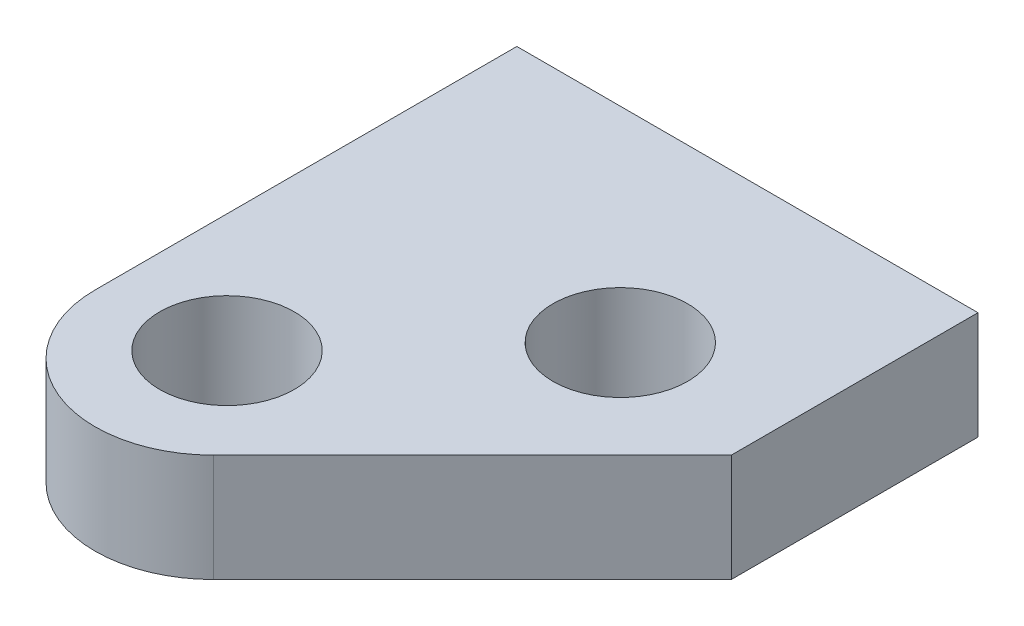
SolidWorks part; units mm, degrees
ref_plane "Piano frontale" through (0, 0, 0) normal (0, 0, 1) x (1, 0, 0)
ref_plane "Piano superiore" through (0, 0, 0) normal (0, 1, 0) x (1, 0, 0)
ref_plane "Piano destro" through (0, 0, 0) normal (1, 0, 0) x (0, 0, -1)
sketch "Schizzo1" plane through (0, 0, 0) normal (0, 1, 0) x (1, 0, 0)
  line L0 (0, 0) -> (0, -37.9)
  line L1 (0, 0) -> (42.8, 0)
  line L2 (42.8, 0) -> (42.8, -22.9)
  line L3 (42.8, -22.9) -> (0, -65.7)
  line L4 (0, -37.9) -> (0, -65.7)
  circle A0 centre (11, -37.9) radius 6.25
  circle A1 centre (28.6, -19) radius 6.25
  dimension "D4" = 12.5
  dimension "D6" = 17.6
  dimension "D8" = 12.5
  dimension "D1" = 42.8
  dimension "D2" = 37.9
  dimension "D3" = 22.9
  dimension "D5" = 11
  dimension "D7" = 19
  dimension "D9" = 45
extrude "Estrusione-Estrusione1" add sketch "Schizzo1" along normal blind 10
fillet "Raccordo1" radius 11 1 edges at (0, 5, 65.7)
sketch "Schizzo2" plane through (0, 0, 0) normal (-1, 0, 0) x (0, 0, 1)
  line L0 (0, 10) -> (0, 0) construction
  circle A0 centre (3, 5) radius 1.8636
  circle A1 centre (9, 5) radius 1.8636
  point P6 (0, 5)
  dimension "D1" = 3
  dimension "D2" = 6
extrude "Taglio-Estrusione1" cut sketch "Schizzo2" against normal blind 10
